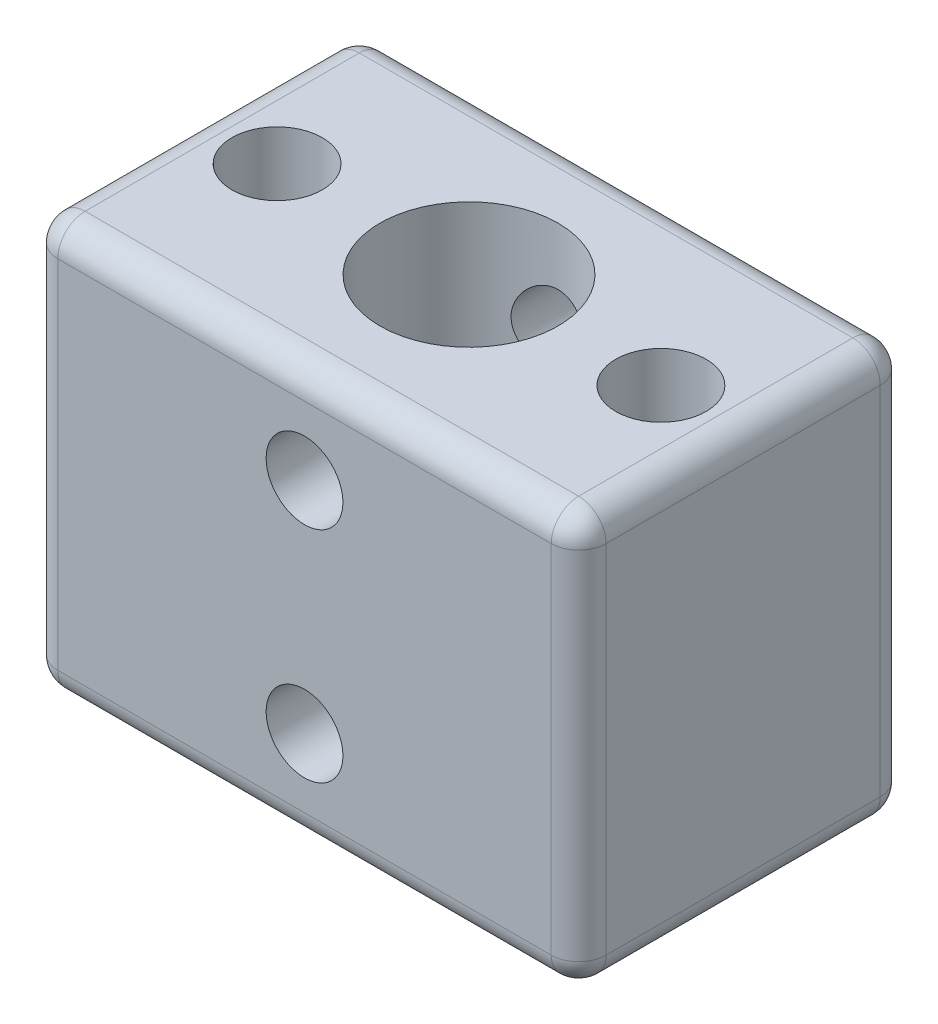
SolidWorks part; units mm, degrees
ref_plane "前视基准面" through (0, 0, 0) normal (0, 0, 1) x (1, 0, 0)
ref_plane "上视基准面" through (0, 0, 0) normal (0, 1, 0) x (1, 0, 0)
ref_plane "右视基准面" through (0, 0, 0) normal (1, 0, 0) x (0, 0, -1)
other "Configuration Table"
sketch "草图1" plane through (0, 0, 0) normal (0, 1, 0) x (1, 0, 0)
  line L0 (0, -2.4917) -> (0, 2.4917) construction
  line L1 (-10, -6) -> (10, -6)
  line L2 (-10, -6) -> (-10, 6)
  line L3 (-10, 6) -> (10, 6)
  line L4 (10, -6) -> (10, 6)
  line L5 (-10, -6) -> (10, 6) construction
  line L6 (-10, 6) -> (10, -6) construction
  circle A0 centre (0, 0) radius 3.25
  circle A1 centre (-7, 0) radius 1.65
  circle A2 centre (7, 0) radius 1.65
  point P0 (0, 0)
  point P13 (0, 0)
  point P17 (0, 0)
  dimension "D1" = 6.5
  dimension "D4" = 3.3
  dimension "D2" = 20
  dimension "D3" = 12
  dimension "D5" = 14
extrude "凸台-拉伸1" add sketch "草图1" along normal mid plane 15
sketch "草图3" plane through (0, 0, -6) normal (0, 0, -1) x (-1, 0, 0)
  line L0 (0, 0) -> (50000, 0) construction
  circle A0 centre (0, 4) radius 1.4
  circle A1 centre (0, -4) radius 1.4
  point P7 (0, 0)
  point P8 (0, 0)
  dimension "D1" = 2.8
  dimension "D2" = 8
  dimension "D3" = 4
extrude "切除-拉伸1" cut sketch "草图3" against normal blind 15
fillet "圆角1" radius 1 12 edges at (10, 0, 6) (10, 7.5, 0) (10, 0, -6) (10, -7.5, 0) (-10, 0, -6) (-10, 7.5, 0) (-10, 0, 6) (-10, -7.5, 0) (0, 7.5, 6) (0, 7.5, -6) (0, -7.5, 6) (0, -7.5, -6)
